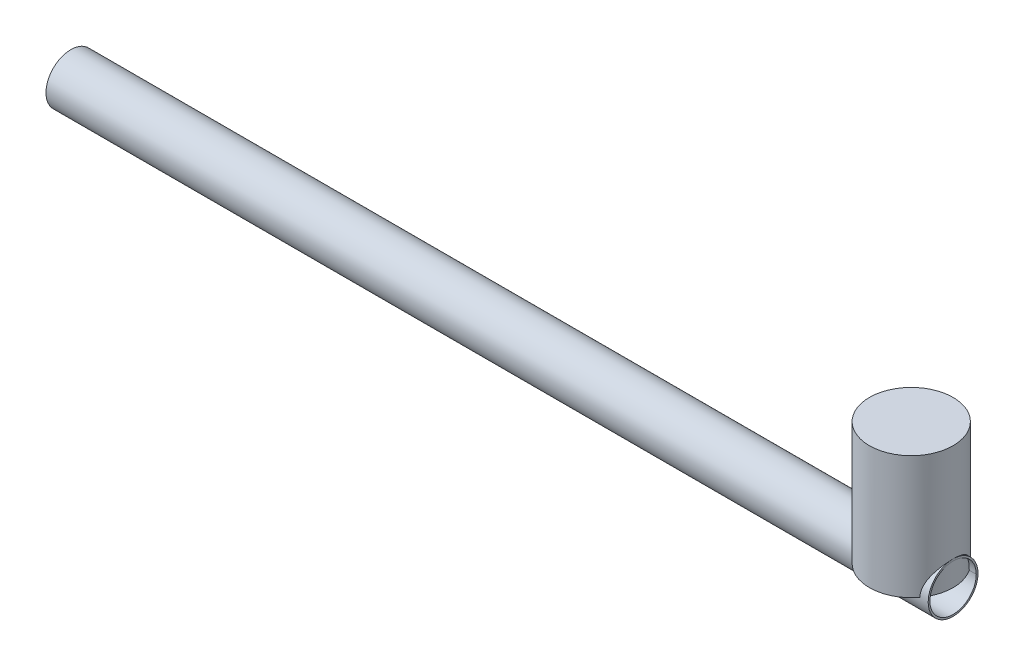
SolidWorks part; units mm, degrees
ref_plane "Front Plane" through (0, 0, 0) normal (0, 0, 1) x (1, 0, 0)
ref_plane "Top Plane" through (0, 0, 0) normal (0, 1, 0) x (1, 0, 0)
ref_plane "Right Plane" through (0, 0, 0) normal (1, 0, 0) x (0, 0, -1)
sketch "Sketch1" plane through (0, 0, 0) normal (1, 0, 0) x (0, 0, -1)
  circle A0 centre (0, 0) radius 12.7
  circle A1 centre (0, 0) radius 11.811
extrude "Boss-Extrude1" add sketch "Sketch1" along normal blind 449.838
sketch "Sketch2" plane through (0, 0, 0) normal (0, 1, 0) x (1, 0, 0)
  circle A0 centre (428.5067, 0) radius 21.3313
extrude "Boss-Extrude2" add sketch "Sketch2" along normal blind 62.7
